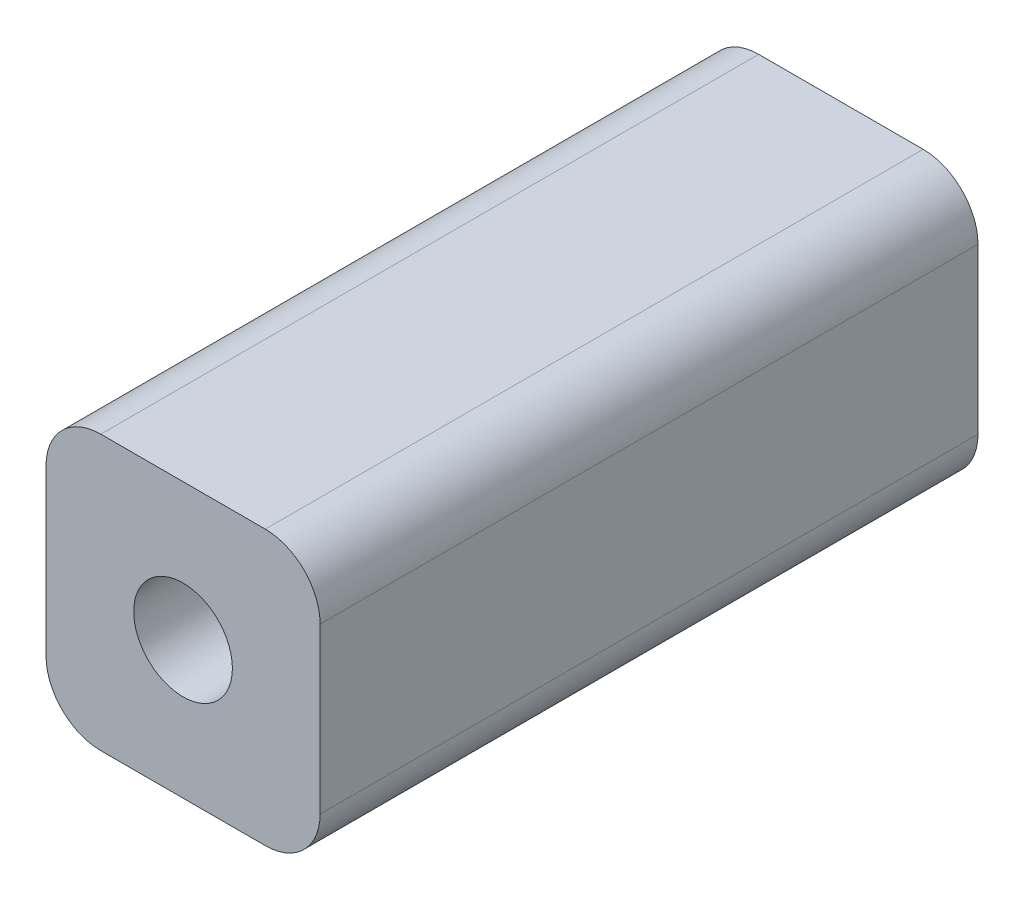
SolidWorks part; units mm, degrees
material "Custom Plastic"
ref_plane "X-Y Datum" through (0, 0, 0) normal (0, 0, 1) x (1, 0, 0)
ref_plane "X-Z Datum" through (0, 0, 0) normal (0, 1, 0) x (1, 0, 0)
ref_plane "Y-Z Datum" through (0, 0, 0) normal (1, 0, 0) x (0, 0, -1)
sketch "Sketch1" plane through (0, 0, 0) normal (0, 0, 1) x (1, 0, 0)
  line L1 (-5, 5) -> (5, 5)
  line L2 (-5, 5) -> (-5, -5)
  line L3 (-5, -5) -> (5, -5)
  line L4 (5, 5) -> (5, -5)
  line L5 (-5, 5) -> (5, -5) construction
  line L6 (-5, -5) -> (5, 5) construction
  circle A0 centre (0, 0) radius 1.5 construction
  point P0 (0, 0)
  point P8 (5.5801, -5.3246)
  dimension "D1" = 3
  dimension "D2" = 10
  dimension "D3" = 10
extrude "Boss-Extrude1" add sketch "Sketch1" along normal blind 24
hole_wizard "M3 Clearance Hole1" positions "Sketch5" profile "Sketch3" hole size "M3" standard "ANSI Metric" end condition through all
sketch "Sketch5" plane through (0, 0, 24) normal (0, 0, 1) x (1, 0, 0)
  point P0 (0, 0)
sketch "Sketch3" plane through (0, 0, 24) normal (1, 0, 0) x (0, -1, 0)
  line L0 (0, 0) -> (0, 24)
  line L1 (0, 24) -> (1.8, 24)
  line L2 (1.8, 24) -> (1.8, 0)
  line L5 (1.8, 0) -> (0, 0)
  line L11 (0, -6.35) -> (0, 107.95) construction
  dimension "Thru Hole Dia." = 3.6
  dimension "Thru Hole Depth" = 24
fillet "Fillet1" radius 2 4 edges at (5, -5, 12) (5, 5, 12) (-5, 5, 12) (-5, -5, 12)
